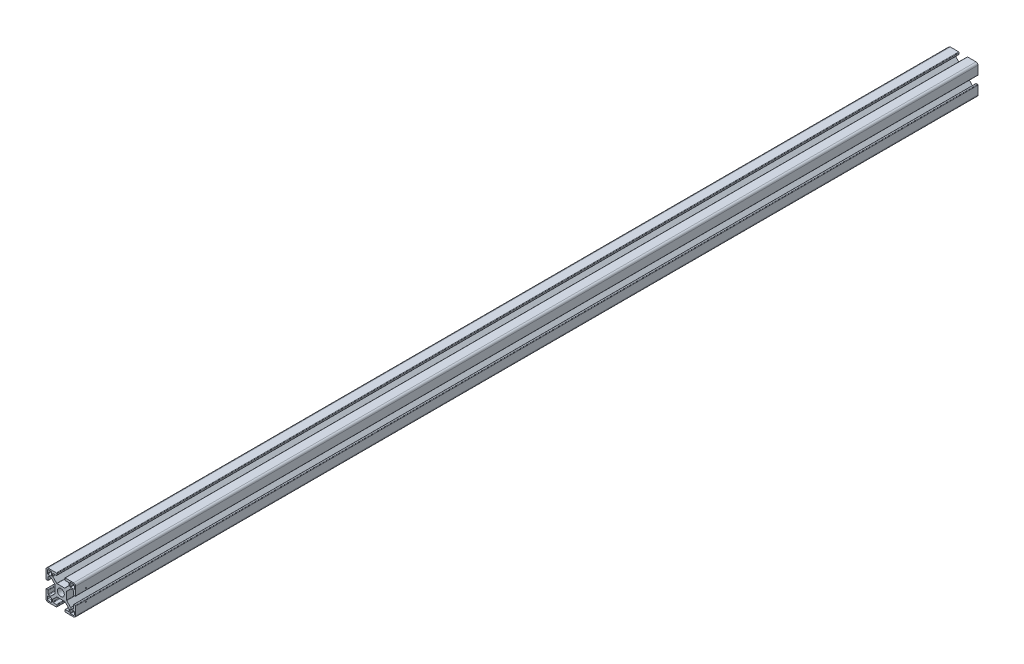
SolidWorks part; units mm, degrees
ref_plane "Front Plane" through (0, 0, 0) normal (0, 0, 1) x (1, 0, 0)
ref_plane "Top Plane" through (0, 0, 0) normal (0, 1, 0) x (1, 0, 0)
ref_plane "Right Plane" through (0, 0, 0) normal (1, 0, 0) x (0, 0, -1)
sketch "Sketch1" plane through (0, 0, 0) normal (0, 0, 1) x (1, 0, 0)
  line L0 (3.9799, -2.4733) -> (3.1981, -1.4942) construction
  line L1 (1.4942, -3.1981) -> (2.4733, -3.9799) construction
  line L2 (-2.4733, -3.9799) -> (-1.4942, -3.1981) construction
  line L3 (-3.1981, -1.4942) -> (-3.9799, -2.4733) construction
  line L4 (-3.9799, 2.4733) -> (-3.1981, 1.4942) construction
  line L5 (-1.4942, 3.1981) -> (-2.4733, 3.9799) construction
  line L6 (2.4733, 3.9799) -> (1.4942, 3.1981) construction
  line L7 (3.1981, 1.4942) -> (3.9799, 2.4733) construction
  line L8 (-12.6999, -13.6999) -> (-9.881, -13.6999)
  line L9 (-13.6999, -9.881) -> (-13.6999, -12.6999)
  line L10 (-9.88, -9.5) -> (-13.3189, -9.5)
  line L11 (-9.5, -13.3189) -> (-9.5, -9.88)
  line L12 (13.6999, -12.6999) -> (13.6999, -9.881)
  line L13 (9.881, -13.6999) -> (12.6999, -13.6999)
  line L14 (9.5, -9.88) -> (9.5, -13.3189)
  line L15 (13.3189, -9.5) -> (9.88, -9.5)
  line L16 (9.88, 9.5) -> (13.3189, 9.5)
  line L17 (9.5, 13.3189) -> (9.5, 9.88)
  line L18 (12.6999, 13.6999) -> (9.881, 13.6999)
  line L19 (13.6999, 9.881) -> (13.6999, 12.6999)
  line L20 (-13.6999, 12.6999) -> (-13.6999, 9.881)
  line L21 (-9.881, 13.6999) -> (-12.6999, 13.6999)
  line L22 (-9.5, 9.88) -> (-9.5, 13.3189)
  line L23 (-13.3189, 9.5) -> (-9.88, 9.5)
  line L24 (14.4999, -4) -> (13.2425, -4)
  line L25 (12.7425, -4.5) -> (12.7425, -7.7325)
  line L26 (12.2428, -8.25) -> (10.2602, -8.25)
  line L27 (9.9066, -8.1035) -> (5.9811, -4.178)
  line L28 (5.8347, -3.8245) -> (5.8347, -1.0125)
  line L29 (5.8347, -1.0125) -> (5.3247, -0.0625) construction
  line L30 (5.3247, -0.0625) -> (5.8347, 0.8875) construction
  line L31 (5.8347, 0.8875) -> (5.8347, 3.8245)
  line L32 (5.9811, 4.178) -> (9.9066, 8.1035)
  line L33 (10.2602, 8.25) -> (12.2428, 8.25)
  line L34 (12.7425, 7.7325) -> (12.7425, 4.5)
  line L35 (13.2425, 4) -> (14.4999, 4)
  line L36 (14.9999, 4.5) -> (14.9999, 12.9999)
  line L37 (12.9999, 14.9999) -> (4.5, 14.9999)
  line L38 (4, 14.4999) -> (4, 13.2425)
  line L39 (4.5, 12.7425) -> (7.7325, 12.7425)
  line L40 (8.25, 12.2428) -> (8.25, 10.2602)
  line L41 (8.1035, 9.9066) -> (4.178, 5.9811)
  line L42 (3.8245, 5.8347) -> (0.95, 5.8347)
  line L43 (0.95, 5.8347) -> (0, 5.3247) construction
  line L44 (0, 5.3247) -> (-0.95, 5.8347) construction
  line L45 (-0.95, 5.8347) -> (-3.8245, 5.8347)
  line L46 (-4.178, 5.9811) -> (-8.1035, 9.9066)
  line L47 (-8.25, 10.2602) -> (-8.25, 12.2428)
  line L48 (-7.7325, 12.7425) -> (-4.5, 12.7425)
  line L49 (-4, 13.2425) -> (-4, 14.4999)
  line L50 (-4.5, 14.9999) -> (-12.9999, 14.9999)
  line L51 (-14.9999, 12.9999) -> (-14.9999, 4.5)
  line L52 (-14.4999, 4) -> (-13.2425, 4)
  line L53 (-12.7425, 4.5) -> (-12.7425, 7.7325)
  line L54 (-12.2428, 8.25) -> (-10.2602, 8.25)
  line L55 (-9.9066, 8.1035) -> (-5.9811, 4.178)
  line L56 (-5.8347, 3.8245) -> (-5.8347, 0.8875)
  line L57 (-5.8347, 0.8875) -> (-5.3247, -0.0625) construction
  line L58 (-5.3247, -0.0625) -> (-5.8347, -1.0125) construction
  line L59 (-5.8347, -1.0125) -> (-5.8347, -3.8245)
  line L60 (-5.9811, -4.178) -> (-9.9066, -8.1035)
  line L61 (-10.2602, -8.25) -> (-12.2428, -8.25)
  line L62 (-12.7425, -7.7325) -> (-12.7425, -4.5)
  line L63 (-13.2425, -4) -> (-14.4999, -4)
  line L64 (-14.9999, -4.5) -> (-14.9999, -12.9999)
  line L65 (-12.9999, -14.9999) -> (-4.5, -14.9999)
  line L66 (-4, -14.4999) -> (-4, -13.2425)
  line L67 (-4.5, -12.7425) -> (-7.7325, -12.7425)
  line L68 (-8.25, -12.2428) -> (-8.25, -10.2602)
  line L69 (-8.1035, -9.9066) -> (-4.178, -5.9811)
  line L70 (-3.8245, -5.8347) -> (-0.95, -5.8347)
  line L71 (-0.95, -5.8347) -> (0, -5.3247) construction
  line L72 (0, -5.3247) -> (0.95, -5.8347) construction
  line L73 (0.95, -5.8347) -> (3.8245, -5.8347)
  line L74 (4.178, -5.9811) -> (8.1035, -9.9066)
  line L75 (8.25, -10.2602) -> (8.25, -12.2428)
  line L76 (7.7325, -12.7425) -> (4.5, -12.7425)
  line L77 (4, -13.2425) -> (4, -14.4999)
  line L78 (4.5, -14.9999) -> (12.9999, -14.9999)
  line L79 (14.9999, -12.9999) -> (14.9999, -4.5)
  line L80 (-5.8347, -1.0125) -> (-5.8347, 0.8875)
  line L81 (-0.95, 5.8347) -> (0.95, 5.8347)
  line L82 (5.8347, 0.8875) -> (5.8347, -1.0125)
  line L83 (-0.95, -5.8347) -> (0.95, -5.8347)
  arc A0 (2.4733, -3.9799) -> (3.9799, -2.4733) centre (3.1422, -3.1422) ccw construction
  arc A1 (-1.4942, -3.1981) -> (1.4942, -3.1981) centre (0, 0) ccw construction
  arc A2 (-3.9799, -2.4733) -> (-2.4733, -3.9799) centre (-3.1422, -3.1422) ccw construction
  arc A3 (-3.1981, 1.4942) -> (-3.1981, -1.4942) centre (0, 0) ccw construction
  arc A4 (-2.4733, 3.9799) -> (-3.9799, 2.4733) centre (-3.1422, 3.1422) ccw construction
  arc A5 (1.4942, 3.1981) -> (-1.4942, 3.1981) centre (0, 0) ccw construction
  arc A6 (3.9799, 2.4733) -> (2.4733, 3.9799) centre (3.1422, 3.1422) ccw construction
  arc A7 (3.1981, -1.4942) -> (3.1981, 1.4942) centre (0, 0) ccw construction
  arc A8 (-13.6999, -12.6999) -> (-12.6999, -13.6999) centre (-12.6999, -12.6999) ccw
  arc A9 (-13.3189, -9.5) -> (-13.6999, -9.881) centre (-13.3189, -9.881) ccw
  arc A10 (-9.5, -9.88) -> (-9.88, -9.5) centre (-9.88, -9.88) ccw
  arc A11 (-9.881, -13.6999) -> (-9.5, -13.3189) centre (-9.881, -13.3189) ccw
  arc A12 (12.6999, -13.6999) -> (13.6999, -12.6999) centre (12.6999, -12.6999) ccw
  arc A13 (9.5, -13.3189) -> (9.881, -13.6999) centre (9.881, -13.3189) ccw
  arc A14 (9.88, -9.5) -> (9.5, -9.88) centre (9.88, -9.88) ccw
  arc A15 (13.6999, -9.881) -> (13.3189, -9.5) centre (13.3189, -9.881) ccw
  arc A16 (9.5, 9.88) -> (9.88, 9.5) centre (9.88, 9.88) ccw
  arc A17 (9.881, 13.6999) -> (9.5, 13.3189) centre (9.881, 13.3189) ccw
  arc A18 (13.6999, 12.6999) -> (12.6999, 13.6999) centre (12.6999, 12.6999) ccw
  arc A19 (13.3189, 9.5) -> (13.6999, 9.881) centre (13.3189, 9.881) ccw
  arc A20 (14.9999, -4.5) -> (14.4999, -4) centre (14.4999, -4.5) ccw
  arc A21 (13.2425, -4) -> (12.7425, -4.5) centre (13.2425, -4.5) ccw
  arc A22 (12.2428, -8.25) -> (12.7425, -7.7325) centre (12.2428, -7.75) ccw
  arc A23 (9.9066, -8.1035) -> (10.2602, -8.25) centre (10.2602, -7.75) ccw
  arc A24 (5.8347, -3.8245) -> (5.9811, -4.178) centre (6.3347, -3.8245) ccw
  arc A25 (5.9811, 4.178) -> (5.8347, 3.8245) centre (6.3347, 3.8245) ccw
  arc A26 (10.2602, 8.25) -> (9.9066, 8.1035) centre (10.2602, 7.75) ccw
  arc A27 (12.7425, 7.7325) -> (12.2428, 8.25) centre (12.2428, 7.75) ccw
  arc A28 (12.7425, 4.5) -> (13.2425, 4) centre (13.2425, 4.5) ccw
  arc A29 (14.4999, 4) -> (14.9999, 4.5) centre (14.4999, 4.5) ccw
  arc A30 (14.9999, 12.9999) -> (12.9999, 14.9999) centre (12.9999, 12.9999) ccw
  arc A31 (4.5, 14.9999) -> (4, 14.4999) centre (4.5, 14.4999) ccw
  arc A32 (4, 13.2425) -> (4.5, 12.7425) centre (4.5, 13.2425) ccw
  arc A33 (8.25, 12.2428) -> (7.7325, 12.7425) centre (7.75, 12.2428) ccw
  arc A34 (8.1035, 9.9066) -> (8.25, 10.2602) centre (7.75, 10.2602) ccw
  arc A35 (3.8245, 5.8347) -> (4.178, 5.9811) centre (3.8245, 6.3347) ccw
  arc A36 (-4.178, 5.9811) -> (-3.8245, 5.8347) centre (-3.8245, 6.3347) ccw
  arc A37 (-8.25, 10.2602) -> (-8.1035, 9.9066) centre (-7.75, 10.2602) ccw
  arc A38 (-7.7325, 12.7425) -> (-8.25, 12.2428) centre (-7.75, 12.2428) ccw
  arc A39 (-4.5, 12.7425) -> (-4, 13.2425) centre (-4.5, 13.2425) ccw
  arc A40 (-4, 14.4999) -> (-4.5, 14.9999) centre (-4.5, 14.4999) ccw
  arc A41 (-12.9999, 14.9999) -> (-14.9999, 12.9999) centre (-12.9999, 12.9999) ccw
  arc A42 (-14.9999, 4.5) -> (-14.4999, 4) centre (-14.4999, 4.5) ccw
  arc A43 (-13.2425, 4) -> (-12.7425, 4.5) centre (-13.2425, 4.5) ccw
  arc A44 (-12.2428, 8.25) -> (-12.7425, 7.7325) centre (-12.2428, 7.75) ccw
  arc A45 (-9.9066, 8.1035) -> (-10.2602, 8.25) centre (-10.2602, 7.75) ccw
  arc A46 (-5.8347, 3.8245) -> (-5.9811, 4.178) centre (-6.3347, 3.8245) ccw
  arc A47 (-5.9811, -4.178) -> (-5.8347, -3.8245) centre (-6.3347, -3.8245) ccw
  arc A48 (-10.2602, -8.25) -> (-9.9066, -8.1035) centre (-10.2602, -7.75) ccw
  arc A49 (-12.7425, -7.7325) -> (-12.2428, -8.25) centre (-12.2428, -7.75) ccw
  arc A50 (-12.7425, -4.5) -> (-13.2425, -4) centre (-13.2425, -4.5) ccw
  arc A51 (-14.4999, -4) -> (-14.9999, -4.5) centre (-14.4999, -4.5) ccw
  arc A52 (-14.9999, -12.9999) -> (-12.9999, -14.9999) centre (-12.9999, -12.9999) ccw
  arc A53 (-4.5, -14.9999) -> (-4, -14.4999) centre (-4.5, -14.4999) ccw
  arc A54 (-4, -13.2425) -> (-4.5, -12.7425) centre (-4.5, -13.2425) ccw
  arc A55 (-8.25, -12.2428) -> (-7.7325, -12.7425) centre (-7.75, -12.2428) ccw
  arc A56 (-8.1035, -9.9066) -> (-8.25, -10.2602) centre (-7.75, -10.2602) ccw
  arc A57 (-3.8245, -5.8347) -> (-4.178, -5.9811) centre (-3.8245, -6.3347) ccw
  arc A58 (4.178, -5.9811) -> (3.8245, -5.8347) centre (3.8245, -6.3347) ccw
  arc A59 (8.25, -10.2602) -> (8.1035, -9.9066) centre (7.75, -10.2602) ccw
  arc A60 (7.7325, -12.7425) -> (8.25, -12.2428) centre (7.75, -12.2428) ccw
  arc A61 (4.5, -12.7425) -> (4, -13.2425) centre (4.5, -13.2425) ccw
  arc A62 (4, -14.4999) -> (4.5, -14.9999) centre (4.5, -14.4999) ccw
  arc A63 (12.9999, -14.9999) -> (14.9999, -12.9999) centre (12.9999, -12.9999) ccw
  arc A64 (-12.6999, 13.6999) -> (-13.6999, 12.6999) centre (-12.6999, 12.6999) ccw
  arc A65 (-9.5, 13.3189) -> (-9.881, 13.6999) centre (-9.881, 13.3189) ccw
  arc A66 (-9.88, 9.5) -> (-9.5, 9.88) centre (-9.88, 9.88) ccw
  arc A67 (-13.6999, 9.881) -> (-13.3189, 9.5) centre (-13.3189, 9.881) ccw
  circle A68 centre (0, 0) radius 3.53
extrude "Boss-Extrude1" add sketch "Sketch1" along normal mid plane 914.4
sketch "Sketch4" plane through (14.9999, 0, 0) normal (1, 0, 0) x (0, 0, -1)
  line L0 (-457.2, 4.5) -> (-457.2, 12.9999) construction
  line L1 (-457.2, 4.5) -> (457.2, 4.5) construction
  line L3 (-457.2, -4.5) -> (457.2, -4.5) construction
  line L6 (-457.2, -12.9999) -> (-457.2, -4.5) construction
  point P0 (-446.77, 6.115)
  point P1 (-446.77, -6.115)
  dimension "D1" = 10.43
  dimension "D2" = 1.615
  dimension "D3" = 1.615
  dimension "D4" = 10.43
hole_wizard "M1.2x0.25 Tapped Hole1" positions "3DSketch1" profile "Sketch5" tap size "M1.2x0.25" standard "ANSI Metric"
sketch3d "3DSketch1"
  point P0 (14.9999, 6.115, 446.77)
  point P3 (14.9999, -6.115, 446.77)
sketch "Sketch5" plane through (14.9999, 6.115, 446.77) normal (0, 1, 0) x (0, 0, -1)
  line L0 (0, 0) -> (0, 2.2575)
  line L1 (0, 2.2575) -> (0.475, 2.2575)
  line L2 (0.475, 2.2575) -> (0.475, 0)
  line L5 (0.475, 0) -> (0, 0)
  line L11 (0, -6.35) -> (0, 107.95) construction
  dimension "Thru Tap Drill Dia." = 0.95
  dimension "Thru Tap Drill Depth" = 2.2575
cosmetic thread "Hole Thread1" parameters "D2"=1.2
cosmetic thread "Hole Thread2" parameters "D2"=1.2
equation "\"D1@Sketch4\"=20.86/2"
equation "\"D2@Sketch4\"=3.23/2"
equation "\"D3@Sketch4\"=\"D2@Sketch4\""
equation "\"D4@Sketch4\"=\"D1@Sketch4\""
